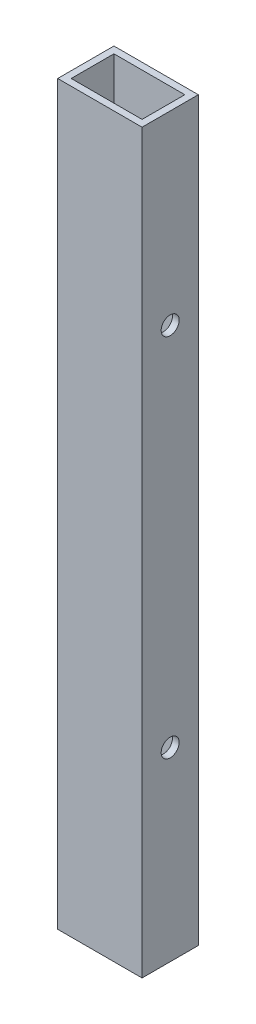
SolidWorks part; units mm, degrees
ref_plane "正面" through (0, 0, 0) normal (0, 0, 1) x (1, 0, 0)
ref_plane "平面" through (0, 0, 0) normal (0, 1, 0) x (1, 0, 0)
ref_plane "右側面" through (0, 0, 0) normal (1, 0, 0) x (0, 0, -1)
sketch "ｽｹｯﾁ1" plane through (0, 0, 0) normal (0, 1, 0) x (1, 0, 0)
  line L0 (-6.3, 3.8) -> (6.3, 3.8)
  line L1 (-7.5, 5) -> (7.5, 5)
  line L2 (-7.5, 5) -> (-7.5, -5)
  line L3 (-7.5, -5) -> (7.5, -5)
  line L4 (7.5, 5) -> (7.5, -5)
  line L5 (-7.5, 5) -> (7.5, -5) construction
  line L6 (-7.5, -5) -> (7.5, 5) construction
  line L7 (6.3, 3.8) -> (6.3, -3.8)
  line L8 (-6.3, -3.8) -> (6.3, -3.8)
  line L9 (-6.3, 3.8) -> (-6.3, -3.8)
  point P0 (0, 0)
  dimension "D1" = 10
  dimension "D2" = 15
  dimension "D3" = 1.2
extrude "ﾎﾞｽ - 押し出し1" add sketch "ｽｹｯﾁ1" along normal mid plane 131
sketch "ｽｹｯﾁ2" plane through (-7.5, 0, 0) normal (-1, 0, 0) x (0, 0, 1)
  line L0 (0, 0) -> (0, 32.5) construction
  circle A0 centre (0, 32.5) radius 1.6
  dimension "D2" = 3.2
  dimension "D1" = 32.5
extrude "ｶｯﾄ - 押し出し1" cut sketch "ｽｹｯﾁ2" against normal mid plane 131
mirror "ﾐﾗｰ1" about plane through (0, 0, 0) normal (0, 1, 0) of "ｶｯﾄ - 押し出し1"
